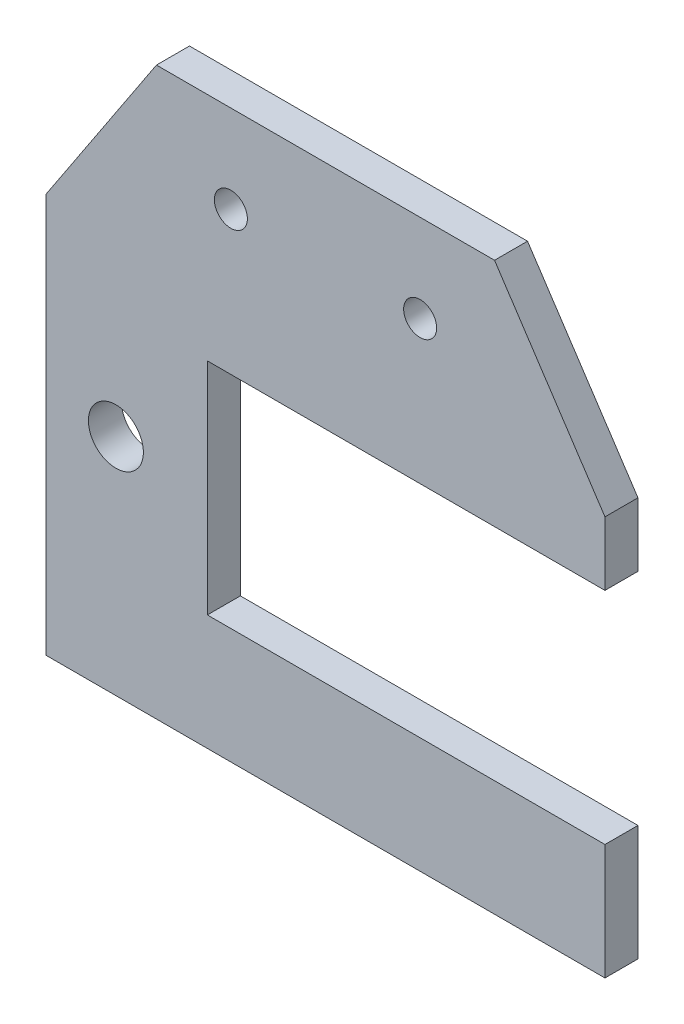
SolidWorks part; units mm, degrees
material "Plain Carbon Steel"
ref_plane "Front Plane" through (0, 0, 0) normal (0, 0, 1) x (1, 0, 0)
ref_plane "Top Plane" through (0, 0, 0) normal (0, 1, 0) x (1, 0, 0)
ref_plane "Right Plane" through (0, 0, 0) normal (1, 0, 0) x (0, 0, -1)
sketch "Sketch1" plane through (0, 0, 0) normal (0, 0, 1) x (1, 0, 0)
  line L0 (0, -12.3213) -> (0, 39.1607)
  line L1 (15.365, 39.1607) -> (-15.365, 39.1607)
  line L2 (-15.365, 39.1607) -> (-25.4023, 23.9787)
  line L3 (-25.4023, 23.9787) -> (-25.4023, -12.3213)
  line L4 (-25.4023, -12.3213) -> (25.4023, -12.3213)
  line L5 (25.4023, 23.9787) -> (25.4023, -12.3213)
  line L6 (15.365, 39.1607) -> (25.4023, 23.9787)
  line L8 (-10.7377, 18.1887) -> (25.4023, 18.1887)
  line L9 (-10.7377, 18.1887) -> (-10.7377, -1.8113)
  line L10 (-10.7377, -1.8113) -> (25.4023, -1.8113)
  line L11 (25.4023, 18.1887) -> (25.4023, -1.8113)
  line L12 (-10.7377, 18.1887) -> (25.4023, -1.8113) construction
  line L13 (-10.7377, -1.8113) -> (25.4023, 18.1887) construction
  circle A0 centre (-19.0523, 8.0787) radius 2.5
  circle A1 centre (-8.6023, 31.1907) radius 1.5
  circle A2 centre (8.6023, 31.1907) radius 1.5
  point P9 (7.3323, 8.1887)
  dimension "D8" = 3
  dimension "D9" = 3
  dimension "D10" = 5
  dimension "D11" = 6.35
  dimension "D12" = 20.4
  dimension "D13" = 7.97
  dimension "D14" = 3
  dimension "D15" = 7.97
  dimension "D16" = 16.8
  dimension "D17" = 16.8
  dimension "D1" = 213.47
  dimension "D2" = 36.3
  dimension "D3" = 18.2
  dimension "D4" = 30.73
  dimension "D5" = 10.51
  dimension "D6" = 20
  dimension "D7" = 36.14
extrude "Boss-Extrude1" add sketch "Sketch1" along normal blind 3 contours L10 L9 L8 L0 L1 L2 L3 L4 A1 A0 | L0 L8 L5 L6 L1 A2 | L10 L0 L4 L5
